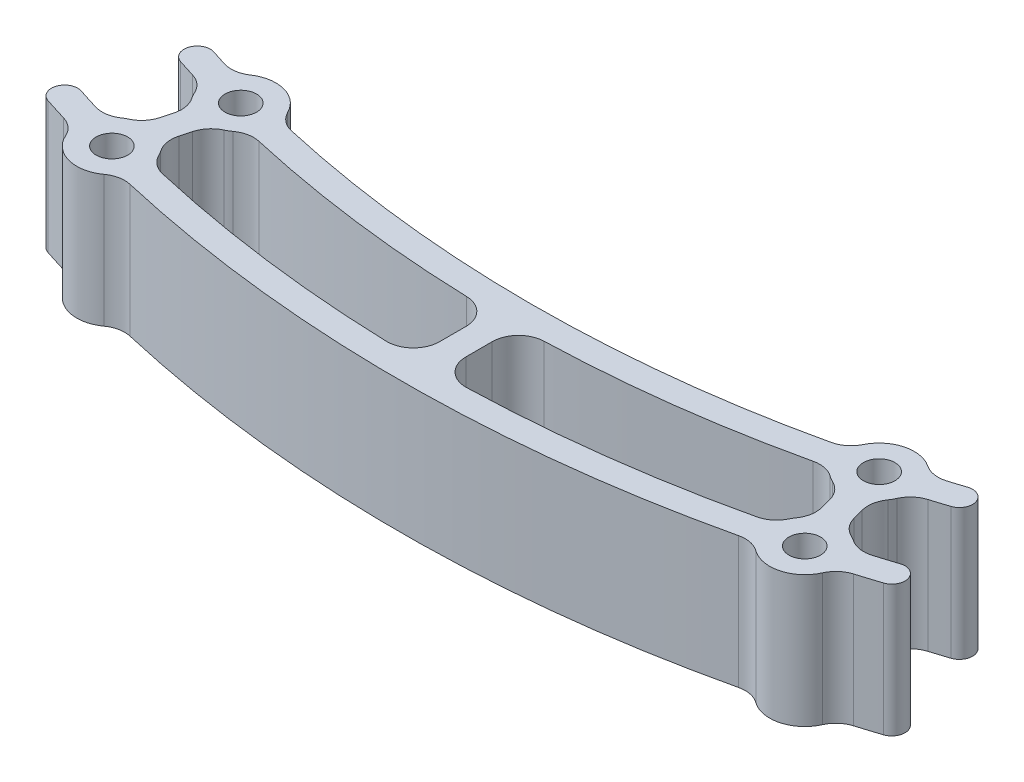
SolidWorks part; units mm, degrees
ref_plane "Front Plane" through (0, 0, 0) normal (0, 0, 1) x (1, 0, 0)
ref_plane "Top Plane" through (0, 0, 0) normal (0, 1, 0) x (1, 0, 0)
ref_plane "Right Plane" through (0, 0, 0) normal (1, 0, 0) x (0, 0, -1)
sketch "Sketch1" plane through (0, 0, 0) normal (0, 1, 0) x (1, 0, 0)
  line L0 (-127, -73.3235) -> (0, 146.647) construction
  line L1 (0, 146.647) -> (127, -73.3235) construction
  line L2 (127, -73.3235) -> (-127, -73.3235) construction
  line L3 (0, -1000) -> (0, 0) construction
  line L4 (-866.0254, 500) -> (0, 0) construction
  line L5 (866.0254, 500) -> (0, 0) construction
  line L6 (0, 0) -> (-147.4456, 39.5079) construction
  line L7 (0, 0) -> (-107.9377, 107.9377) construction
  line L8 (0, 0) -> (-39.5079, 147.4456) construction
  line L9 (0, 0) -> (39.5079, 147.4456) construction
  line L10 (0, 0) -> (107.9377, 107.9377) construction
  line L11 (0, 0) -> (147.4456, 39.5079) construction
  line L12 (0, 0) -> (147.4456, -39.5079) construction
  line L13 (0, 0) -> (107.9377, -107.9377) construction
  line L14 (0, 0) -> (39.5079, -147.4456) construction
  line L15 (0, 0) -> (-39.5079, -147.4456) construction
  line L16 (0, 0) -> (-107.9377, -107.9377) construction
  line L17 (0, 0) -> (-147.4456, -39.5079) construction
  line L18 (0, 0) -> (-47.1705, -145.1759) construction
  line L20 (47.1705, -145.1759) -> (0, 0) construction
  circle A0 centre (0, 0) radius 146.647 construction
  circle A1 centre (0, 0) radius 152.647 construction
  circle A2 centre (0, 0) radius 140.647 construction
  arc A8 (-47.1705, -145.1759) -> (47.1705, -145.1759) centre (0, 0) ccw construction
  point P2 (0, -73.3235)
  point P10 (-63.5, 36.6617)
  point P15 (63.5, 36.6617)
  point P16 (0, 0)
  point P27 (0, 0)
  point P28 (0, 0)
  point P31 (0, 0)
  point P32 (-14.6431, -130.3745)
  point P33 (-52.2083, -144.3567)
  point P34 (52.2083, -144.9307)
  point P35 (0, 0)
  dimension "D2" = 6
  dimension "D3" = 6
  dimension "D1" = 254
  dimension "D4" = 12
  dimension "D5" = 15
  dimension "D8" = 3
  dimension "D9" = 3
sketch "Sketch2" plane through (0, 0, 0) normal (0, 1, 0) x (1, 0, 0)
  line L0 (47.1705, -145.1759) -> (0, 0) construction
  line L1 (0, 0) -> (-47.1705, -145.1759) construction
  arc A0 (43.4623, -133.7632) -> (-43.4623, -133.7632) centre (0, 0) cw construction
  circle A1 centre (0, 0) radius 140.647 construction
  arc A2 (-43.9258, -135.1898) -> (43.9258, -135.1898) centre (0, 0) ccw
  arc A3 (-42.9988, -132.3366) -> (42.9988, -132.3366) centre (0, 0) ccw
  arc A4 (-42.9988, -132.3366) -> (-43.9258, -135.1898) centre (-43.4623, -133.7632) ccw
  arc A5 (43.9258, -135.1898) -> (42.9988, -132.3366) centre (43.4623, -133.7632) ccw
  arc A6 (-47.1705, -145.1759) -> (47.1705, -145.1759) centre (0, 0) ccw construction
  arc A7 (-47.634, -146.6025) -> (47.634, -146.6025) centre (0, 0) ccw
  arc A8 (-46.707, -143.7493) -> (46.707, -143.7493) centre (0, 0) ccw
  arc A9 (-46.707, -143.7493) -> (-47.634, -146.6025) centre (-47.1705, -145.1759) ccw
  arc A10 (47.634, -146.6025) -> (46.707, -143.7493) centre (47.1705, -145.1759) ccw
  point P10 (0, -140.647)
  point P15 (0, -152.647)
  point P24 (-47.1705, -145.1759)
  dimension "D1" = 3
  dimension "D2" = 3
extrude "Boss-Extrude1" add sketch "Sketch2" along normal blind 15
sketch "Sketch3" plane through (0, 0, 0) normal (0, 1, 0) x (1, 0, 0)
  line L0 (0, 0) -> (-39.5079, -147.4456) construction
  line L1 (0, 0) -> (39.5079, -147.4456) construction
  circle A0 centre (-36.4021, -135.8545) radius 4
  circle A1 centre (-39.5079, -147.4456) radius 4
  circle A2 centre (36.4021, -135.8545) radius 4
  circle A3 centre (39.5079, -147.4456) radius 4
  circle A4 centre (0, 0) radius 140.647 construction
  circle A5 centre (0, 0) radius 152.647 construction
  point P12 (0, 0)
  point P14 (0, 0)
  point P17 (0, 0)
  point P18 (0, 0)
  dimension "D1" = 8
extrude "Boss-Extrude2" add sketch "Sketch3" along normal up to surface (15 mm away) up to face at (0, 15, 136.9733)
sketch "Sketch4" plane through (0, 0, 0) normal (0, 1, 0) x (1, 0, 0)
  line L0 (-37.7242, -134.993) -> (-34.8264, -135.7694)
  line L1 (-37.7242, -134.993) -> (-41.0837, -147.5308)
  line L2 (-34.8264, -135.7694) -> (-38.1859, -148.3072)
  line L3 (-41.0837, -147.5308) -> (-38.1859, -148.3072)
  line L4 (37.7242, -134.993) -> (34.8264, -135.7694)
  line L5 (37.7242, -134.993) -> (41.0837, -147.5308)
  line L6 (34.8264, -135.7694) -> (38.1859, -148.3072)
  line L7 (41.0837, -147.5308) -> (38.1859, -148.3072)
  line L8 (36.2753, -135.3812) -> (39.6348, -147.919) construction
  line L9 (-36.2753, -135.3812) -> (-39.6348, -147.919) construction
  line L10 (0, 0) -> (-39.5079, -147.4456) construction
  line L11 (0, 0) -> (39.5079, -147.4456) construction
  line L12 (0, -201000) -> (0, 0) construction
  line L13 (1.5, -153.137) -> (-1.5, -153.137)
  line L14 (1.5, -153.137) -> (1.5, -140.1569)
  line L15 (1.5, -140.1569) -> (-1.5, -140.1569)
  line L16 (-1.5, -153.137) -> (-1.5, -140.1569)
  line L17 (1.5, -153.137) -> (-1.5, -140.1569) construction
  line L18 (1.5, -140.1569) -> (-1.5, -153.137) construction
  circle A2 centre (0, 0) radius 146.647 construction
  point P0 (-37.955, -141.6501)
  point P19 (37.955, -141.6501)
  point P20 (0, -146.647)
  dimension "D1" = 3
  dimension "D2" = 3
extrude "Boss-Extrude3" add sketch "Sketch4" along normal up to surface (15 mm away) up to face at (0, 15, 135.7149)
hole_wizard "M3 Clearance Hole1" positions "Sketch5" profile "Sketch6" hole size "M3" standard "ANSI Metric" end condition through all
sketch "Sketch5" plane through (0, 15, 0) normal (0, 1, 0) x (1, 0, 0)
  line L0 (0, 0) -> (-39.5079, -147.4456) construction
  line L1 (0, 0) -> (39.5079, -147.4456) construction
  circle A0 centre (0, 0) radius 140.647 construction
  point P0 (-36.4021, -135.8545)
  point P6 (-39.5079, -147.4456)
  point P9 (39.5079, -147.4456)
  point P12 (36.4021, -135.8545)
sketch "Sketch6" plane through (-36.4021, 15, 135.8545) normal (1, 0, 0) x (0, 0, 1)
  line L0 (0, 0) -> (0, 15)
  line L1 (0, 15) -> (1.8, 15)
  line L2 (1.8, 15) -> (1.8, 0)
  line L5 (1.8, 0) -> (0, 0)
  line L11 (0, -6.35) -> (0, 107.95) construction
  dimension "Thru Hole Dia." = 3.6
  dimension "Thru Hole Depth" = 15
fillet "Fillet1" radius 3 28 edges at (-39.5635, 7.5, 133.4039) (-32.4389, 7.5, 135.3129) (32.4389, 7.5, 135.3129) (39.5635, 7.5, 133.4039) (35.5442, 7.5, 146.9082) (42.6719, 7.5, 144.9983) (39.9971, 7.5, 143.4757) (38.8107, 7.5, 139.0481) (37.0993, 7.5, 144.2521) (-1.5, 7.5, 151.1395) (1.5, 7.5, 151.1395) (1.5, 7.5, 142.1391) (35.913, 7.5, 139.8245) (-1.5, 7.5, 142.1391) (-42.6719, 7.5, 144.9983) (-35.5442, 7.5, 146.9082) (-37.0993, 7.5, 144.2521) (-33.1772, 7.5, 138.221) (-40.3782, 7.5, 136.2915) (-38.8107, 7.5, 139.0481) (-39.9971, 7.5, 143.4757) (33.1772, 7.5, 138.221) (40.3782, 7.5, 136.2915) (36.2855, 7.5, 149.8154) (43.4836, 7.5, 147.8867) (-35.913, 7.5, 139.8245) (-43.4836, 7.5, 147.8867) (-36.2855, 7.5, 149.8154)
